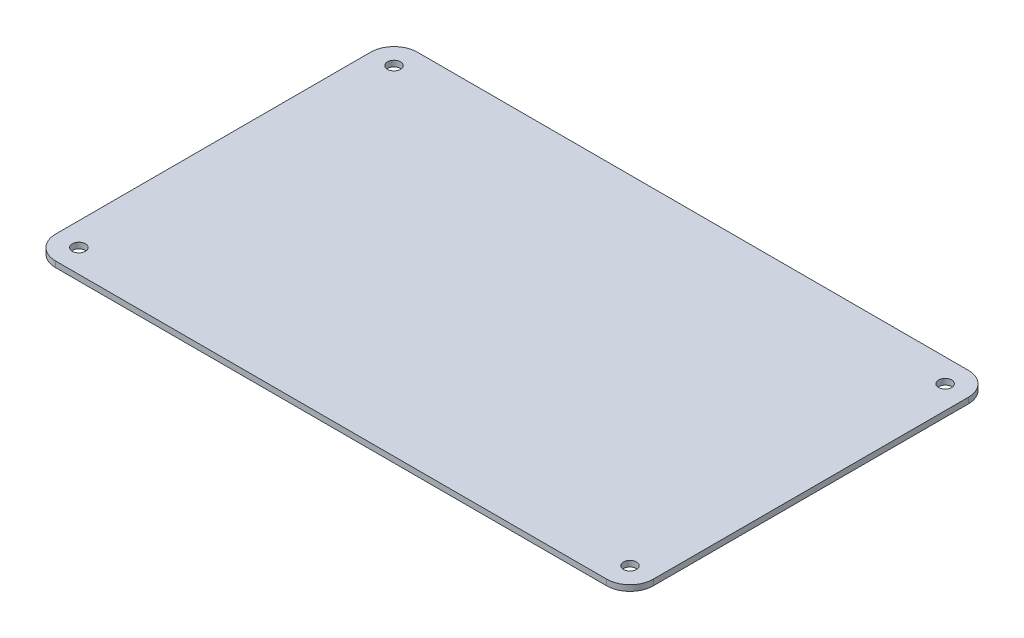
SolidWorks part; units mm, degrees
ref_plane "Front Plane" through (0, 0, 0) normal (0, 0, 1) x (1, 0, 0)
ref_plane "Top Plane" through (0, 0, 0) normal (0, 1, 0) x (1, 0, 0)
ref_plane "Right Plane" through (0, 0, 0) normal (1, 0, 0) x (0, 0, -1)
sketch "Sketch1" plane through (0, 0, 0) normal (0, 1, 0) x (1, 0, 0)
  line L0 (-179.291, 0) -> (179.291, 0) construction
  line L1 (-150.2918, 85.9396) -> (150.2918, 85.9396) construction
  line L2 (-150.2918, 85.9396) -> (-150.2918, -85.9396) construction
  line L3 (-150.2918, -85.9396) -> (150.2918, -85.9396) construction
  line L4 (150.2918, 85.9396) -> (150.2918, -85.9396) construction
  line L5 (-150.2918, 85.9396) -> (150.2918, -85.9396) construction
  line L6 (-150.2918, -85.9396) -> (150.2918, 85.9396) construction
  line L7 (-150.2918, 98.6396) -> (150.2918, 98.6396)
  line L8 (-162.9918, 85.9396) -> (-162.9918, -85.9396)
  line L9 (-150.2918, -98.6396) -> (150.2918, -98.6396)
  line L10 (162.9918, 85.9396) -> (162.9918, -85.9396)
  line L13 (0, -108.5036) -> (0, 108.5036) construction
  arc A0 (-150.2918, 98.6396) -> (-162.9918, 85.9396) centre (-150.2918, 85.9396) ccw
  arc A1 (-150.2918, -98.6396) -> (-162.9918, -85.9396) centre (-150.2918, -85.9396) cw
  arc A2 (150.2918, -98.6396) -> (162.9918, -85.9396) centre (150.2918, -85.9396) ccw
  arc A3 (150.2918, 98.6396) -> (162.9918, 85.9396) centre (150.2918, 85.9396) cw
  point P4 (0, 0)
  point P11 (0, 0)
  point P13 (0, 0)
  dimension "D1" = 300.5836
  dimension "D2" = 171.8793
  dimension "D3" = 12.7
  dimension "D4" = 12.7
extrude "Boss-Extrude1" add sketch "Sketch1" along normal blind 3.175
hole_wizard "1/4 Clearance Hole1" positions "Sketch2" profile "Sketch3" hole size "1/4" standard "ANSI Inch" end condition through all
sketch "Sketch2" plane through (0, 3.175, 0) normal (0, 1, 0) x (1, 0, 0)
  point P0 (-150.2918, 85.9396)
  point P3 (150.2918, 85.9396)
  point P6 (150.2918, -85.9396)
  point P9 (-150.2918, -85.9396)
sketch "Sketch3" plane through (-150.2918, 3.175, -85.9396) normal (1, 0, 0) x (0, 0, 1)
  line L0 (0, 0) -> (0, 3.175)
  line L1 (0, 3.175) -> (3.5712, 3.175)
  line L2 (3.5712, 3.175) -> (3.5712, 0)
  line L5 (3.5712, 0) -> (0, 0)
  line L11 (0, -6.35) -> (0, 107.95) construction
  dimension "Thru Hole Dia." = 7.1425
  dimension "Thru Hole Depth" = 3.175
equation "\"width\"= 6.7669in"
equation "\"length\"= 11.834in"
equation "\"D1@Sketch1\"=\"length\""
equation "\"D2@Sketch1\"=\"width\""
